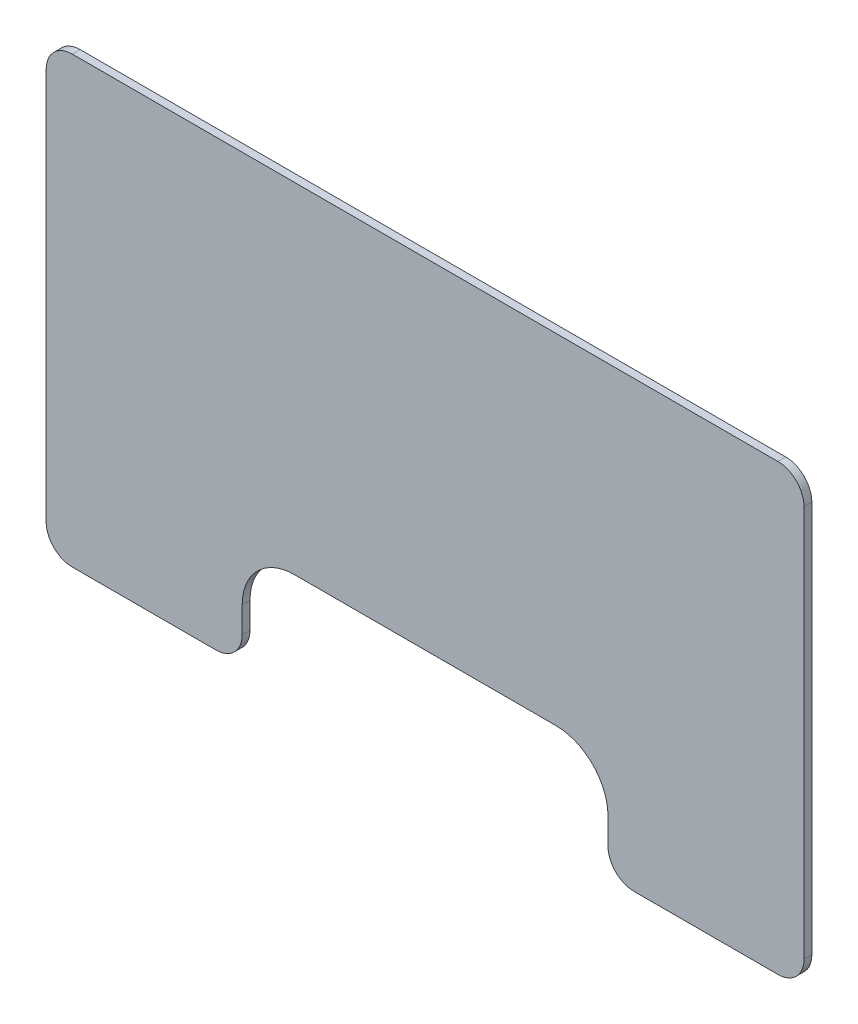
SolidWorks part; units mm, degrees
ref_plane "Спереди" through (0, 0, 0) normal (0, 0, 1) x (1, 0, 0)
ref_plane "Сверху" through (0, 0, 0) normal (0, 1, 0) x (1, 0, 0)
ref_plane "Справа" through (0, 0, 0) normal (1, 0, 0) x (0, 0, -1)
sketch "Эскиз1" plane through (0, 0, 0) normal (0, 0, 1) x (1, 0, 0)
  line L0 (-72.5, 0) -> (-72.5, 85) construction
  line L1 (-5, 0) -> (-32.5, 0)
  line L2 (0, 5) -> (0, 80)
  line L3 (-5, 85) -> (-140, 85)
  line L4 (-145, 5) -> (-145, 80)
  line L5 (-112.5, 0) -> (-140, 0)
  line L7 (-107.5, 5) -> (-107.5, 10)
  line L8 (-97.5, 20) -> (-47.5, 20)
  line L9 (-37.5, 5) -> (-37.5, 10)
  arc A0 (0, 80) -> (-5, 85) centre (-5, 80) ccw
  arc A1 (-5, 0) -> (0, 5) centre (-5, 5) ccw
  arc A2 (-140, 0) -> (-145, 5) centre (-140, 5) cw
  arc A3 (-140, 85) -> (-145, 80) centre (-140, 80) ccw
  arc A4 (-32.5, 0) -> (-37.5, 5) centre (-32.5, 5) cw
  arc A5 (-107.5, 5) -> (-112.5, 0) centre (-112.5, 5) cw
  arc A6 (-47.5, 20) -> (-37.5, 10) centre (-47.5, 10) cw
  arc A7 (-107.5, 10) -> (-97.5, 20) centre (-97.5, 10) cw
  point P11 (0, 0)
  point P24 (-107.5, 0)
  point P27 (-37.5, 20)
  point P30 (-107.5, 20)
  dimension "D3" = 5
  dimension "D6" = 5
  dimension "D7" = 10
  dimension "D1" = 145
  dimension "D2" = 85
  dimension "D4" = 70
  dimension "D5" = 20
extrude "Бобышка-Вытянуть1" add sketch "Эскиз1" along normal blind 1.5
